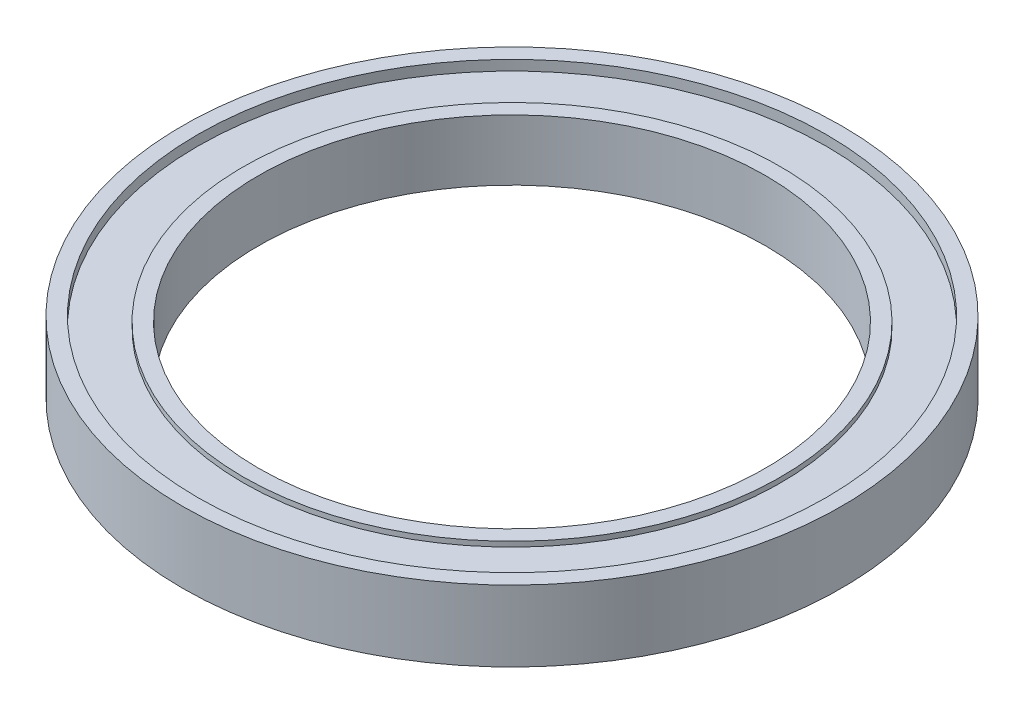
SolidWorks part; units mm, degrees
ref_plane "Alzado" through (0, 0, 0) normal (0, 0, 1) x (1, 0, 0)
ref_plane "Planta" through (0, 0, 0) normal (0, 1, 0) x (1, 0, 0)
ref_plane "Vista lateral" through (0, 0, 0) normal (1, 0, 0) x (0, 0, -1)
sketch "Croquis1" plane through (0, 0, 0) normal (0, 1, 0) x (1, 0, 0)
  circle A0 centre (0, 0) radius 32.5
  circle A1 centre (0, 0) radius 25
extrude "Saliente-Extruir1" add sketch "Croquis1" along normal blind 7
sketch "Internal seal sketch" plane through (0, 7, 0) normal (0, 1, 0) x (1, 0, 0)
  circle A0 centre (0, 0) radius 26.5
  circle A1 centre (0, 0) radius 31
  dimension "D1" = 53
  dimension "D2" = 62
ref_plane "Symmetry plane" through (0, 3.5, 0) normal (0, 1, 0) x (1, 0, 0)
extrude "Cortar-Extruir1" cut sketch "Internal seal sketch" against normal blind 1
sketch "Internal adjust sketch" plane through (0, 7, 0) normal (0, 1, 0) x (1, 0, 0)
  circle A0 centre (0, 0) radius 26.5
  circle A1 centre (0, 0) radius 25
extrude "Cortar-Extruir2" cut sketch "Internal adjust sketch" against normal blind 0.5
mirror "Simetría1" about plane through (0, 3.5, 0) normal (0, 1, 0) of "Cortar-Extruir2", "Cortar-Extruir1"
